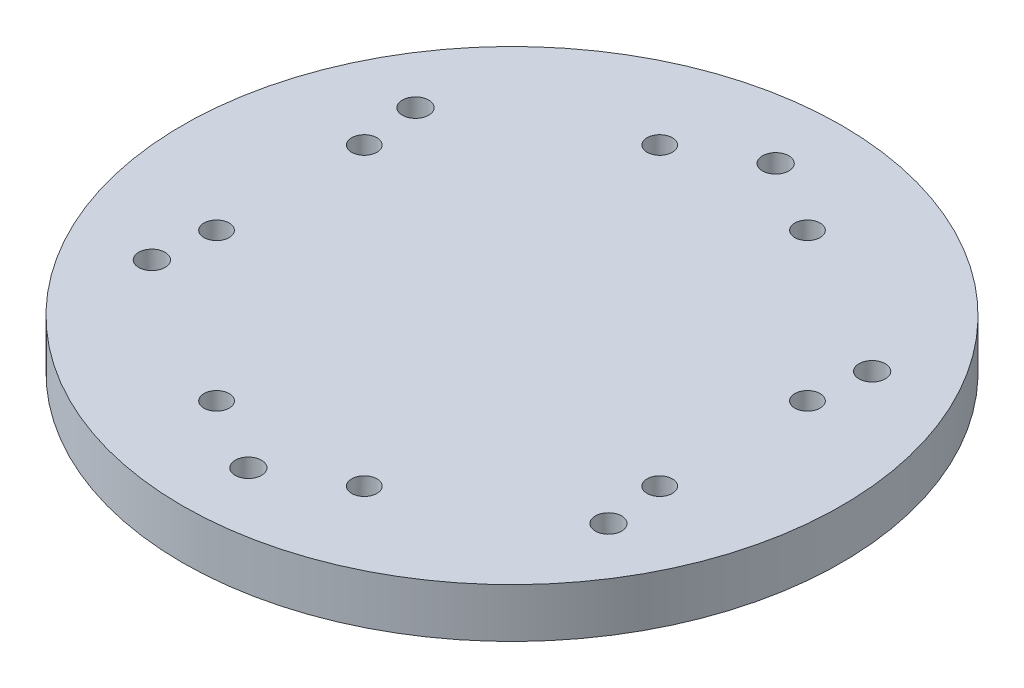
SolidWorks part; units mm, degrees
other "Markup1"
sketch "Sketch10" plane through (-85, 12.7, 85) normal (0, 1, 0) x (-1, 0, 0)
material "ASTM A36 Steel"
ref_plane "Front Plane" through (0, 0, 0) normal (0, 0, 1) x (1, 0, 0)
ref_plane "Top Plane" through (0, 0, 0) normal (0, 1, 0) x (1, 0, 0)
ref_plane "Right Plane" through (0, 0, 0) normal (1, 0, 0) x (0, 0, -1)
sketch "Sketch1" plane through (0, 0, 0) normal (0, 1, 0) x (1, 0, 0)
  circle A0 centre (0, 0) radius 85
  dimension "D3" = 170
extrude "Boss-Extrude1" add sketch "Sketch1" along normal blind 12.7
hole_wizard "M8x1.25 Tapped Hole1" positions "Sketch3" profile "Sketch5" tap size "M8x1.25" standard "ANSI Metric" end condition through all
sketch "Sketch3" plane through (0, 12.7, 0) normal (0, 1, 0) x (1, 0, 0)
  point P0 (0, 68)
  point P5 (0, 68)
  dimension "D1" = 68
cosmetic thread "Hole Thread1"
cosmetic thread "Hole Thread15"
sketch "Sketch5" plane through (0, 12.7, -68) normal (1, 0, 0) x (0, 0, 1)
  line L0 (0, 0) -> (0, 12.7)
  line L1 (0, 12.7) -> (3.4, 12.7)
  line L2 (3.4, 12.7) -> (3.4, 0)
  line L5 (3.4, 0) -> (0, 0)
  line L11 (0, -6.35) -> (0, 107.95) construction
  dimension "Thru Tap Drill Dia." = 6.8
  dimension "Thru Tap Drill Depth" = 12.7
sketch "Sketch13" plane through (0, 0, 0) normal (0, 0, 1) x (1, 0, 0)
  line L0 (0, 0) -> (0, 28.9496) construction
pattern_circular "CirPattern3" count 6 every 60 about axis through (0, 0, 0) along (0, 1, 0) of "M8x1.25 Tapped Hole1"
cosmetic thread "Hole Thread21"
cosmetic thread "Hole Thread22"
cosmetic thread "Hole Thread23"
cosmetic thread "Hole Thread24"
cosmetic thread "Hole Thread25"
cosmetic thread "Hole Thread26"
cosmetic thread "Hole Thread27"
cosmetic thread "Hole Thread28"
cosmetic thread "Hole Thread29"
cosmetic thread "Hole Thread30"
hole_wizard "5/16-18 Tapped Hole1" positions "Sketch8" profile "Sketch9" tap size "5/16-18" standard "ANSI Inch" end condition through all
sketch "Sketch8" plane through (0, 0, 0) normal (0, -1, 0) x (-1, 0, 0)
  point P0 (-19.05, 57.15)
  point P3 (19.05, 57.15)
  dimension "D1" = 57.15
  dimension "D2" = 19.05
  dimension "D3" = 57.15
  dimension "D4" = 19.05
sketch "Sketch9" plane through (19.05, 0, -57.15) normal (1, 0, 0) x (0, 0, -1)
  line L0 (0, 0) -> (0, 12.7)
  line L1 (0, 12.7) -> (3.2639, 12.7)
  line L2 (3.2639, 12.7) -> (3.2639, 0)
  line L5 (3.2639, 0) -> (0, 0)
  line L11 (0, -6.35) -> (0, 107.95) construction
  dimension "Thru Tap Drill Dia." = 6.5278
  dimension "Thru Tap Drill Depth" = 12.7
cosmetic thread "Hole Thread7"
cosmetic thread "Hole Thread8"
pattern_circular "CirPattern2" count 4 over 360 about axis through (0, 0, 0) along (0, 1, 0) of "5/16-18 Tapped Hole1"
cosmetic thread "Hole Thread9"
cosmetic thread "Hole Thread10"
cosmetic thread "Hole Thread11"
cosmetic thread "Hole Thread12"
cosmetic thread "Hole Thread13"
cosmetic thread "Hole Thread14"
equation "\"D1@Sketch3\"=(136/2)"
equation "\"D3@Sketch8\"=\"D1@Sketch8\""
equation "\"D4@Sketch8\"=\"D2@Sketch8\""
